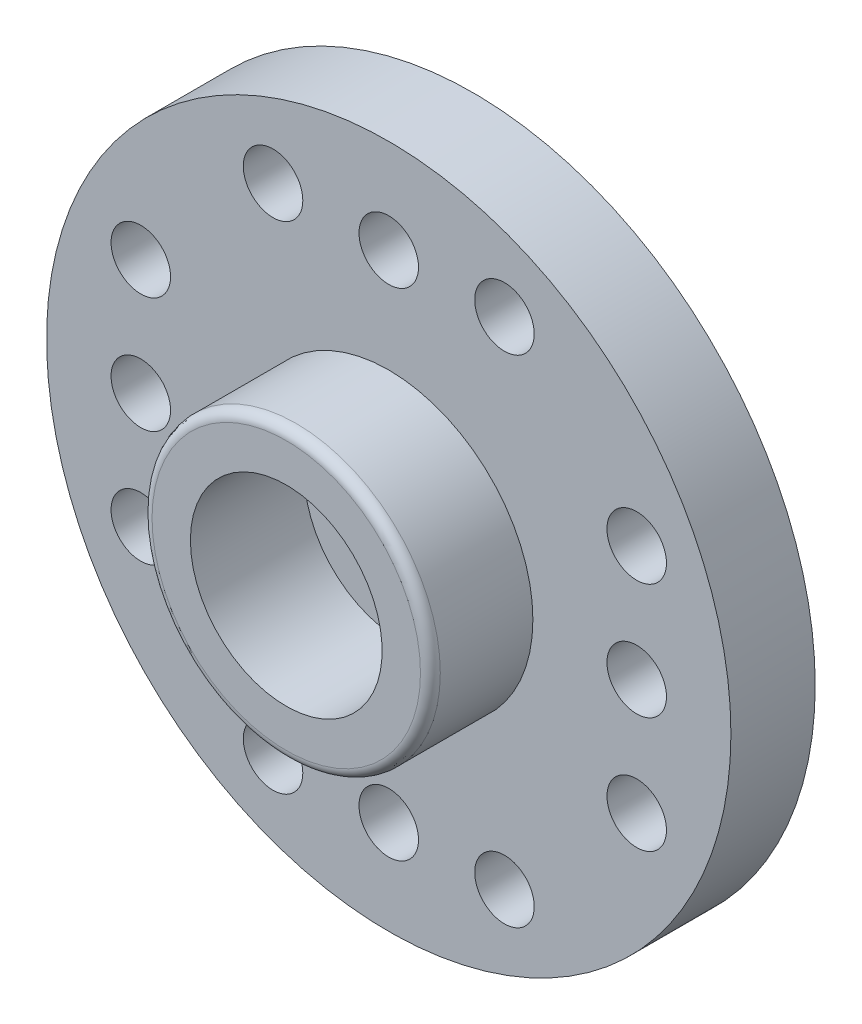
SolidWorks part; units mm, degrees
ref_plane "Plano frontal" through (0, 0, 0) normal (0, 0, 1) x (1, 0, 0)
ref_plane "Plano superior" through (0, 0, 0) normal (0, 1, 0) x (1, 0, 0)
ref_plane "Plano direito" through (0, 0, 0) normal (1, 0, 0) x (0, 0, -1)
sketch "Esboço1" plane through (0, 0, 0) normal (0, 0, 1) x (1, 0, 0)
  circle A0 centre (0, 0) radius 10.35
  dimension "D1" = 20.7
extrude "Ressalto-extrusão1" add sketch "Esboço1" along normal blind 2.55
sketch "Esboço2" plane through (0, 0, 2.55) normal (0, 0, 1) x (1, 0, 0)
  circle A0 centre (0, 0) radius 4.36
  circle A1 centre (0, 0) radius 2.9
  dimension "D1" = 8.72
  dimension "D2" = 5.8
extrude "Ressalto-extrusão2" add sketch "Esboço2" along normal blind 3.1
sketch "Esboço3" plane through (0, 0, 0) normal (0, 0, -1) x (-1, 0, 0)
  circle A0 centre (0, 0) radius 4.36
extrude "Ressalto-extrusão3" add sketch "Esboço3" along normal blind 0.49
chamfer "Chanfro1" distance 0.48 angle 45 1 edges at (-4.36, 0, -0.49)
sketch "Esboço4" plane through (0, 0, -0.49) normal (0, 0, -1) x (-1, 0, 0)
  circle A0 centre (0, 0) radius 3.5
  dimension "D1" = 7
extrude "Corte-extrusão1" cut sketch "Esboço4" against normal blind 1.2
sketch "Esboço5" plane through (0, 0, 2.55) normal (0, 0, 1) x (1, 0, 0)
  circle A0 centre (0, 0) radius 1.25
  dimension "D1" = 2.5
extrude "Corte-extrusão2" cut sketch "Esboço5" against normal blind 7.2 and the other way blind 7 contours A0
fillet "Filete1" radius 0.3 1 edges at (4.36, 0, 5.65)
sketch "Esboço6" plane through (0, 0, 2.55) normal (0, 0, 1) x (1, 0, 0)
  line L0 (0, 0) -> (0, 7.5) construction
  line L1 (0, 0) -> (7.5, 0) construction
  line L2 (0, 7.5) -> (-3.5, 7.5) construction
  line L3 (-3.5, 7.5) -> (-3.5, 4.7844) construction
  line L4 (7.5, 0) -> (7.5, 3.5) construction
  line L5 (7.5, 3.5) -> (5.8642, 3.5) construction
  line L6 (0, 7.5) -> (3.5, 7.5) construction
  line L7 (3.5, 7.5) -> (3.5, 5.7734) construction
  line L8 (7.5, 0) -> (7.5, -3.5) construction
  line L9 (7.5, -3.5) -> (6.2968, -3.5) construction
  line L10 (-7.5, -3.5) -> (-6.2968, -3.5) construction
  line L11 (-7.5, 0) -> (-7.5, -3.5) construction
  line L12 (-7.5, 0) -> (-7.5, 3.5) construction
  line L13 (3.5, -7.5) -> (3.5, -5.7734) construction
  line L14 (0, -7.5) -> (3.5, -7.5) construction
  line L15 (0, -7.5) -> (-3.5, -7.5) construction
  circle A0 centre (0, 7.5) radius 0.9
  circle A1 centre (-3.5, 7.5) radius 0.9
  circle A2 centre (3.5, 7.5) radius 0.9
  circle A3 centre (7.5, 0) radius 0.9
  circle A4 centre (7.5, 3.5) radius 0.9
  circle A5 centre (7.5, -3.5) radius 0.9
  circle A6 centre (-7.5, -3.5) radius 0.9
  circle A7 centre (-7.5, 3.5) radius 0.9
  circle A8 centre (-7.5, 0) radius 0.9
  circle A9 centre (3.5, -7.5) radius 0.9
  circle A10 centre (-3.5, -7.5) radius 0.9
  circle A11 centre (0, -7.5) radius 0.9
  dimension "D5" = 1.8
  dimension "D6" = 1.8
  dimension "D7" = 1.8
  dimension "D10" = 1.8
  dimension "D11" = 1.8
  dimension "D12" = 1.8
  dimension "D1" = 7.5
  dimension "D2" = 7.5
  dimension "D3" = 3.5
  dimension "D4" = 3.5
  dimension "D8" = 3.5
  dimension "D9" = 3.5
extrude "Corte-extrusão3" cut sketch "Esboço6" against normal blind 4.2 and the other way blind 2
sketch "Esboço8" plane through (0, 0, 5.65) normal (0, 0, 1) x (1, 0, 0)
  circle A0 centre (0, 0) radius 2.9
extrude "Corte-extrusão4" cut sketch "Esboço8" against normal blind 3.45
